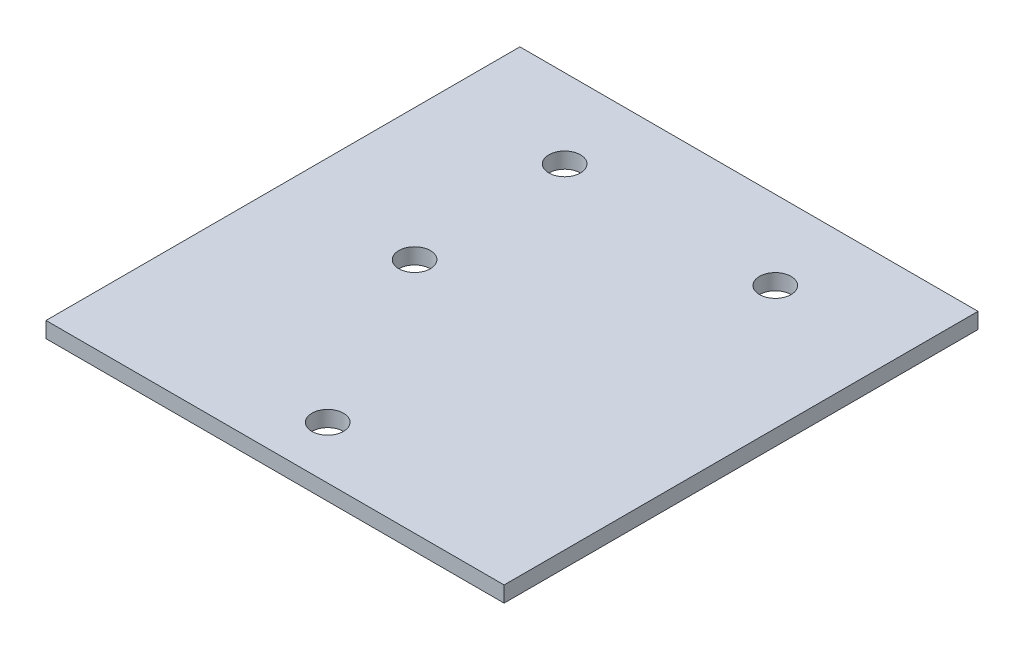
SolidWorks part; units mm, degrees
ref_plane "Front Plane" through (0, 0, 0) normal (0, 0, 1) x (1, 0, 0)
ref_plane "Top Plane" through (0, 0, 0) normal (0, 1, 0) x (1, 0, 0)
ref_plane "Right Plane" through (0, 0, 0) normal (1, 0, 0) x (0, 0, -1)
sketch "Sketch1" plane through (0, 0, 0) normal (0, 1, 0) x (1, 0, 0)
  line L1 (-43.5, -45) -> (43.5, -45)
  line L2 (-43.5, -45) -> (-43.5, 45)
  line L3 (-43.5, 45) -> (43.5, 45)
  line L4 (43.5, -45) -> (43.5, 45)
  line L5 (-43.5, -45) -> (43.5, 45) construction
  line L6 (-43.5, 45) -> (43.5, -45) construction
  point P0 (0, 0)
  dimension "D1" = 87
  dimension "D2" = 90
extrude "Boss-Extrude1" add sketch "Sketch1" along normal blind 3 separate body
sketch "Sketch2" plane through (0, 3, 0) normal (0, 1, 0) x (1, 0, 0)
  line L2 (-43.5, 45) -> (-43.5, -45) construction
  line L3 (43.5, 45) -> (-43.5, 45) construction
  circle A0 centre (-18.5, 0) radius 3
  dimension "D1" = 6
  dimension "D2" = 25
  dimension "D3" = 45
extrude "Cut-Extrude1" cut sketch "Sketch2" against normal through all
sketch "Sketch3" plane through (0, 0, 0) normal (0, -1, 0) x (1, 0, 0)
  line L0 (0, -1.65) -> (0, 1.65) construction
  line L2 (-43.5, 45) -> (43.5, 45) construction
  line L4 (43.5, -45) -> (-43.5, -45) construction
  circle A0 centre (0, 35) radius 3
  circle A1 centre (-20, -30) radius 3
  circle A2 centre (20, -30) radius 3
  dimension "D1" = 6
  dimension "D2" = 10
  dimension "D3" = 20
  dimension "D4" = 20
  dimension "D5" = 15
  dimension "D6" = 15
extrude "Cut-Extrude2" cut sketch "Sketch3" against normal through all
